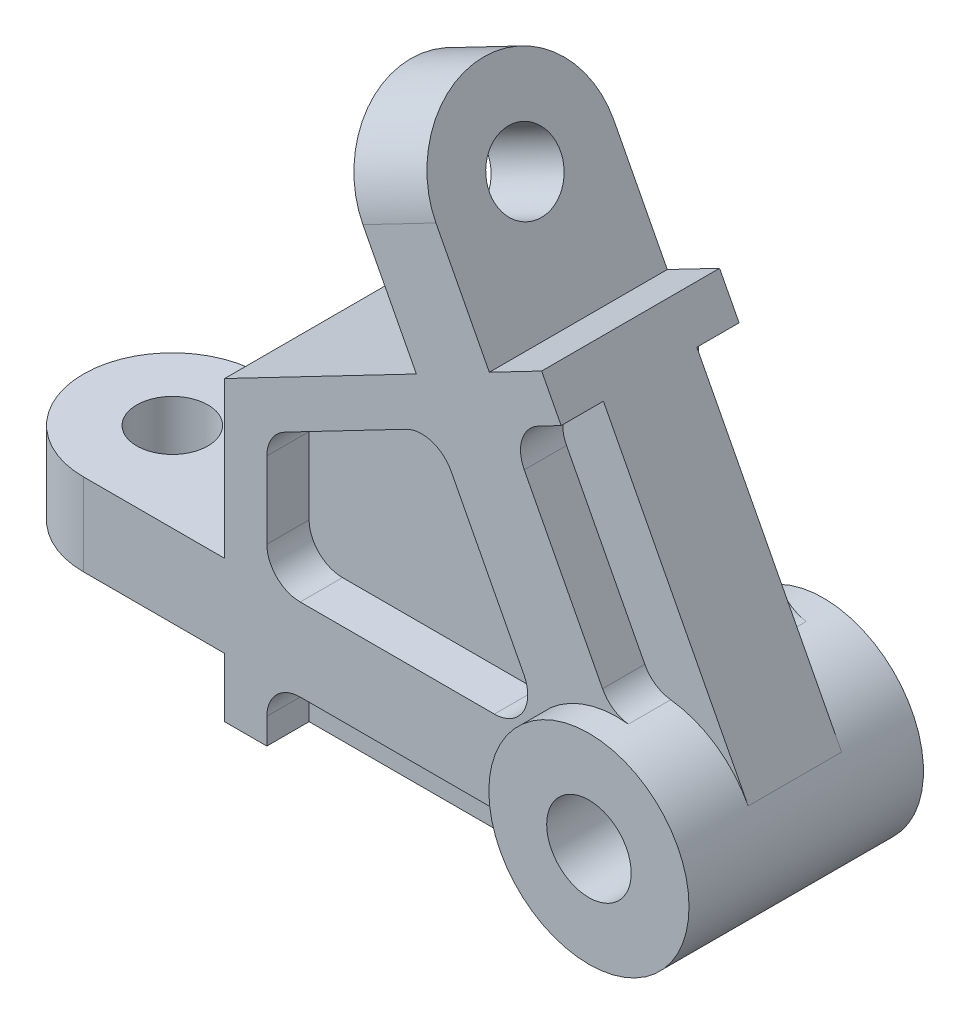
SolidWorks part; units mm, degrees
material "Alliage 1060"
ref_plane "Plan de face" through (0, 0, 0) normal (0, 0, 1) x (1, 0, 0)
ref_plane "Plan de dessus" through (0, 0, 0) normal (0, 1, 0) x (1, 0, 0)
ref_plane "Plan de droite" through (0, 0, 0) normal (1, 0, 0) x (0, 0, -1)
sketch "Esquisse1" plane through (0, 0, 0) normal (0, 0, 1) x (1, 0, 0)
  line L0 (19.9577, 10.3893) -> (-16.9819, 81.3498)
  line L1 (-16.9819, 81.3498) -> (-28.7348, 75.2316)
  line L2 (-28.7348, 75.2316) -> (-49.9755, 116.0345)
  line L3 (-49.9755, 116.0345) -> (-66.3852, 107.4922)
  line L4 (-66.3852, 107.4922) -> (-45.1445, 66.6893)
  line L5 (-45.1445, 66.6893) -> (-88.25, 44.25)
  line L6 (-88.25, 44.25) -> (-88.25, 9.25)
  line L7 (-88.25, 9.25) -> (-140, 9.25)
  line L8 (-140, 9.25) -> (-140, -9.25)
  line L9 (-140, -9.25) -> (-88.25, -9.25)
  line L10 (-88.25, -9.25) -> (-88.25, -22.5605)
  line L11 (-88.25, -22.5605) -> (0.0154, -22.5)
  line L12 (0, 0) -> (-140, 0)
  line L13 (0, 0) -> (-58.1803, 111.7634)
  circle A0 centre (0, 0) radius 22.5
  circle A1 centre (0, 0) radius 9.5
  dimension "D1" = 19
  dimension "D2" = 45
  dimension "D3" = 18.5
  dimension "D4" = 18.5
  dimension "D5" = 9.25
  dimension "D6" = 62.5
  dimension "D7" = 35
  dimension "D8" = 140
  dimension "D9" = 126
  dimension "D10" = 0
  dimension "D11" = 0
  dimension "D12" = 51.75
extrude "Boss.-Extru.1" add sketch "Esquisse1" along normal blind 40 contours A0 L0 L1 L2 L3 L13 | A0 L13 L3 L4 L5 L6 L7 L8 L12 | A0 L12 L8 L9 L10 L11 | A1 L12 A0 L13 | A1 L13 A0 L12
sketch "Esquisse2" plane through (8.2049, 4.2712, 0) normal (0.887, 0.4617, 0) x (0, 0, -1)
  line L0 (-40, 126) -> (0, 126) construction
  line L1 (0, 79.9995) -> (0, 126) construction
  line L6 (0, 79.9995) -> (0, 126)
  line L7 (0, 126) -> (-40, 126)
  line L8 (-40, 126) -> (-40, 79.9995)
  line L9 (-40, 79.9995) -> (0, 79.9995)
  line L10 (0, 79.9995) -> (0, 126)
  line L11 (0, 126) -> (-40, 126)
  line L12 (-40, 126) -> (-40, 79.9995)
  line L13 (-40, 79.9995) -> (0, 79.9995)
  circle A0 centre (-20, 106) radius 8
  circle A1 centre (-20, 106) radius 20
  line M8 (0, 126) -> (-40, 126)
  line M9 (-40, 126) -> (-40, 79.9995)
  dimension "D1" = 16
  dimension "D2" = 40
  dimension "D3" = 0
extrude "Enlèv. mat.-Extru.1" cut sketch "Esquisse2" against normal through all contours A0 | A1 L11 M9 | A1 L10 M8
sketch "Esquisse3" plane through (0, 9.25, 0) normal (0, 1, 0) x (1, 0, 0)
  line L0 (-140, -40) -> (-140, 0) construction
  line L1 (-88.25, 0) -> (-140, 0) construction
  line L6 (-88.25, 0) -> (-140, 0)
  line L7 (-140, 0) -> (-140, -40)
  line L8 (-140, -40) -> (-88.25, -40)
  line L9 (-88.25, -40) -> (-88.25, 0)
  line L10 (-88.25, 0) -> (-140, 0)
  line L11 (-140, 0) -> (-140, -40)
  line L12 (-140, -40) -> (-88.25, -40)
  line L13 (-88.25, -40) -> (-88.25, 0)
  circle A0 centre (-120, -20) radius 8
  circle A1 centre (-120, -20) radius 20
  line M8 (-140, 0) -> (-140, -40)
  line M9 (-140, -40) -> (-88.25, -40)
  dimension "D1" = 40
  dimension "D2" = 16
  dimension "D3" = 0
extrude "Enlèv. mat.-Extru.2" cut sketch "Esquisse3" against normal through all contours A1 L10 M8 | A1 L11 M9 | A0
sketch "Esquisse4" plane through (0, 0, 40) normal (0, 0, 1) x (1, 0, 0)
  line L0 (19.9577, 10.3893) -> (-16.9819, 81.3498) construction
  line L1 (-16.9819, 81.3498) -> (-28.7348, 75.2316) construction
  line L2 (-28.7348, 75.2316) -> (-49.9755, 116.0345) construction
  line L3 (-49.9755, 116.0345) -> (-66.3852, 107.4922) construction
  line L4 (-66.3852, 107.4922) -> (-45.1445, 66.6893) construction
  line L5 (-45.1445, 66.6893) -> (-88.25, 44.25) construction
  line L6 (-88.25, 44.25) -> (-88.25, 9.25) construction
  line L7 (-88.25, 9.25) -> (-140, 9.25) construction
  line L8 (-140, 9.25) -> (-140, -9.25) construction
  line L9 (-140, -9.25) -> (-88.25, -9.25) construction
  line L10 (-88.25, -9.25) -> (-88.25, -22.5605) construction
  line L11 (-88.25, -22.5605) -> (0.0154, -22.5) construction
  line L12 (0, 0) -> (-140, 0) construction
  line L13 (0, 0) -> (-58.1803, 111.7634) construction
  line L14 (19.9577, 10.3893) -> (-16.9819, 81.3498)
  line L15 (-16.9819, 81.3498) -> (-28.7348, 75.2316)
  line L16 (-28.7348, 75.2316) -> (-49.9755, 116.0345)
  line L17 (-49.9755, 116.0345) -> (-66.3852, 107.4922)
  line L18 (-66.3852, 107.4922) -> (-45.1445, 66.6893)
  line L19 (-45.1445, 66.6893) -> (-88.25, 44.25)
  line L20 (-88.25, 44.25) -> (-88.25, 9.25)
  line L21 (-88.25, 9.25) -> (-140, 9.25)
  line L22 (-140, 9.25) -> (-140, -9.25)
  line L23 (-140, -9.25) -> (-88.25, -9.25)
  line L24 (-88.25, -9.25) -> (-88.25, -22.5605)
  line L25 (-88.25, -22.5605) -> (0.0154, -22.5)
  line L26 (0, 0) -> (-140, 0)
  line L27 (0, 0) -> (-58.1803, 111.7634)
  circle A1 centre (0, 0) radius 22.5
  circle A2 centre (0, 0) radius 22.5
  circle A3 centre (0, 0) radius 9.5
  circle A4 centre (0, 0) radius 9.5
  arc M7 (0.0154, -22.5) -> (19.9577, 10.3893) centre (0, 0) ccw
  circle M16 centre (0, 0) radius 9.5
  dimension "D1" = 0
  dimension "D2" = 0
extrude "Boss.-Extru.2" add sketch "Esquisse4" along normal blind 6.35 contours A2 L27 L26 M7 M16 | L27 A2 L26 M16
sketch "Esquisse5" plane through (0, 0, 0) normal (0, 0, -1) x (-1, 0, 0)
  line L0 (-19.9577, 10.3893) -> (16.9819, 81.3498) construction
  line L1 (16.9819, 81.3498) -> (28.7348, 75.2316) construction
  line L2 (28.7348, 75.2316) -> (49.9755, 116.0345) construction
  line L3 (49.9755, 116.0345) -> (66.3852, 107.4922) construction
  line L4 (66.3852, 107.4922) -> (45.1445, 66.6893) construction
  line L5 (45.1445, 66.6893) -> (88.25, 44.25) construction
  line L6 (88.25, 44.25) -> (88.25, 9.25) construction
  line L7 (88.25, 9.25) -> (140, 9.25) construction
  line L8 (140, 9.25) -> (140, -9.25) construction
  line L9 (140, -9.25) -> (88.25, -9.25) construction
  line L10 (88.25, -9.25) -> (88.25, -22.5605) construction
  line L11 (88.25, -22.5605) -> (-0.0154, -22.5) construction
  line L12 (0, 0) -> (140, 0) construction
  line L13 (0, 0) -> (58.1803, 111.7634) construction
  line L14 (-19.9577, 10.3893) -> (16.9819, 81.3498)
  line L15 (16.9819, 81.3498) -> (28.7348, 75.2316)
  line L16 (28.7348, 75.2316) -> (49.9755, 116.0345)
  line L17 (49.9755, 116.0345) -> (66.3852, 107.4922)
  line L18 (66.3852, 107.4922) -> (45.1445, 66.6893)
  line L19 (45.1445, 66.6893) -> (88.25, 44.25)
  line L20 (88.25, 44.25) -> (88.25, 9.25)
  line L21 (88.25, 9.25) -> (140, 9.25)
  line L22 (140, 9.25) -> (140, -9.25)
  line L23 (140, -9.25) -> (88.25, -9.25)
  line L24 (88.25, -9.25) -> (88.25, -22.5605)
  line L25 (88.25, -22.5605) -> (-0.0154, -22.5)
  line L26 (0, 0) -> (140, 0)
  line L27 (0, 0) -> (58.1803, 111.7634)
  circle A1 centre (0, 0) radius 22.5
  circle A2 centre (0, 0) radius 22.5
  circle A3 centre (0, 0) radius 9.5
  circle A4 centre (0, 0) radius 9.5
  arc M13 (-19.9577, 10.3893) -> (-0.0154, -22.5) centre (0, 0) ccw
  circle M16 centre (0, 0) radius 9.5
  dimension "D1" = 0
  dimension "D2" = 0
extrude "Boss.-Extru.3" add sketch "Esquisse5" along normal blind 6.35 contours L26 A2 L27 M16 | L27 A2 L26 M13 M16
sketch "Esquisse6" plane through (0, 0, 40) normal (0, 0, 1) x (1, 0, 0)
  line L0 (-12.5953, 72.9232) -> (-17.6956, 70.2681)
  line L1 (19.9577, 10.3893) -> (-16.9819, 81.3498) construction
  line L2 (-20.8851, 60.1525) -> (-3.2874, 26.3475)
  line L3 (-88.25, -22.5605) -> (0.0154, -22.5) construction
  line L4 (-16.9819, 81.3498) -> (-28.7348, 75.2316) construction
  line L5 (-28.7348, 75.2316) -> (-40.7405, 98.2943) construction
  line L6 (-40.7405, 98.2943) -> (-57.1502, 89.752) construction
  line L7 (-57.1502, 89.752) -> (-45.1445, 66.6893) construction
  line L8 (-45.1445, 66.6893) -> (-88.25, 44.25) construction
  line L9 (-88.25, 44.25) -> (-88.25, 9.25) construction
  line L10 (-88.25, 9.25) -> (-120, 9.25) construction
  line L11 (-120, 9.25) -> (-120, -9.25) construction
  line L12 (-120, -9.25) -> (-88.25, -9.25) construction
  line L13 (-88.25, -9.25) -> (-88.25, -22.5605) construction
  line L14 (-88.25, -22.5605) -> (0.0154, -22.5)
  line L15 (19.9577, 10.3893) -> (-16.9819, 81.3498)
  line L16 (-16.9819, 81.3498) -> (-28.7348, 75.2316)
  line L17 (-28.7348, 75.2316) -> (-40.7405, 98.2943)
  line L18 (-40.7405, 98.2943) -> (-57.1502, 89.752)
  line L19 (-57.1502, 89.752) -> (-45.1445, 66.6893)
  line L20 (-45.1445, 66.6893) -> (-88.25, 44.25)
  line L21 (-88.25, 44.25) -> (-88.25, 9.25)
  line L22 (-88.25, 9.25) -> (-120, 9.25)
  line L23 (-120, 9.25) -> (-120, -9.25)
  line L24 (-120, -9.25) -> (-88.25, -9.25)
  line L25 (-88.25, -9.25) -> (-88.25, -22.5605)
  line L26 (-37.2948, 51.6101) -> (-20.9506, 20.2131)
  line L27 (-27.6031, 9.25) -> (-71.25, 9.25)
  line L28 (-78.75, 16.75) -> (-78.75, 33.9341)
  line L29 (-74.7131, 40.5867) -> (-47.4105, 54.7996)
  line L30 (-78.75, -22.554) -> (-78.75, -16.75)
  line L31 (-71.25, -9.25) -> (-24.8885, -9.25)
  line L32 (0, 0) -> (-120, 0)
  line L33 (0, 0) -> (-48.9454, 94.0231)
  arc A0 (-17.6956, 70.2681) -> (-20.8851, 60.1525) centre (-14.2325, 63.6156) ccw
  circle A1 centre (0, 0) radius 22.5 construction
  arc A2 (19.9577, 10.3893) -> (0.0154, -22.5) centre (0, 0) ccw construction
  arc A3 (-18.6664, -12.5625) -> (2.5239, 22.358) centre (0, 0) ccw
  arc A4 (19.9577, 10.3893) -> (-1.2659, 22.4644) centre (0, 0) ccw
  arc A5 (-20.9506, 20.2131) -> (-27.6031, 9.25) centre (-27.6031, 16.75) cw
  arc A6 (-37.2948, 51.6101) -> (-47.4105, 54.7996) centre (-43.9474, 48.147) ccw
  arc A7 (-71.25, 9.25) -> (-78.75, 16.75) centre (-71.25, 16.75) cw
  arc A8 (-78.75, 33.9341) -> (-74.7131, 40.5867) centre (-71.25, 33.9341) cw
  arc A9 (-78.75, -16.75) -> (-71.25, -9.25) centre (-71.25, -16.75) cw
  arc A10 (-10.3893, 19.9577) -> (-22.5, 0) centre (0, 0) ccw
  arc A11 (-10.3893, 19.9577) -> (-22.5, 0) centre (0, 0) ccw
  arc A12 (-20.5107, -9.25) -> (0.0154, -22.5) centre (0, 0) ccw
  arc A13 (-3.2874, 26.3475) -> (2.5239, 22.358) centre (3.3652, 29.8107) ccw
  arc A14 (-24.8885, -9.25) -> (-18.6664, -12.5625) centre (-24.8885, -16.75) cw
  arc M30 (0.0154, -22.5) -> (19.9577, 10.3893) centre (0, 0) cw
  line M31 (19.9577, 10.3893) -> (-16.9819, 81.3498)
  dimension "D1" = 7.5
  dimension "D2" = 7.5
  dimension "D5" = 7.5
  dimension "D10" = 7.5
  dimension "D13" = 7.5
  dimension "D3" = 9.5
  dimension "D4" = 9.5
  dimension "D6" = 9.5
  dimension "D7" = 9.25
  dimension "D8" = 9.25
  dimension "D9" = 9.25
  dimension "D11" = 9.25
  dimension "D12" = 9.5
extrude "Enlèv. mat.-Extru.3" cut sketch "Esquisse6" against normal blind 9.5 contours A8 L28 A7 L27 A5 L26 A6 L29 | L0 A0 L2 M30 M31 | A9 L30 L14 L31 M30
sketch "Esquisse9" plane through (0, 0, 0) normal (0, 0, -1) x (-1, 0, 0)
  line L0 (24.8885, -9.25) -> (71.25, -9.25) construction
  line L1 (78.75, -16.75) -> (78.75, -22.554) construction
  line L2 (78.75, -22.554) -> (-0.0154, -22.5) construction
  line L3 (20.8851, 60.1525) -> (3.2874, 26.3475) construction
  line L4 (-19.9577, 10.3893) -> (12.5953, 72.9232) construction
  line L5 (12.5953, 72.9232) -> (17.6956, 70.2681) construction
  line L6 (78.75, 33.9341) -> (78.75, 16.75) construction
  line L7 (71.25, 9.25) -> (27.6031, 9.25) construction
  line L8 (20.9506, 20.2131) -> (37.2948, 51.6101) construction
  line L9 (47.4105, 54.7996) -> (74.7131, 40.5867) construction
  line L10 (-0.0154, -22.5) -> (88.25, -22.5605) construction
  line L11 (88.25, -22.5605) -> (88.25, -9.25) construction
  line L12 (88.25, -9.25) -> (120, -9.25) construction
  line L13 (120, -9.25) -> (120, 9.25) construction
  line L14 (120, 9.25) -> (88.25, 9.25) construction
  line L15 (88.25, 9.25) -> (88.25, 44.25) construction
  line L16 (88.25, 44.25) -> (45.1445, 66.6893) construction
  line L17 (45.1445, 66.6893) -> (57.1502, 89.752) construction
  line L18 (57.1502, 89.752) -> (40.7405, 98.2943) construction
  line L19 (40.7405, 98.2943) -> (28.7348, 75.2316) construction
  line L20 (28.7348, 75.2316) -> (16.9819, 81.3498) construction
  line L21 (16.9819, 81.3498) -> (-19.9577, 10.3893) construction
  line L22 (24.8885, -9.25) -> (71.25, -9.25)
  line L23 (78.75, -16.75) -> (78.75, -22.554)
  line L24 (78.75, -22.554) -> (-0.0154, -22.5)
  line L25 (20.8851, 60.1525) -> (3.2874, 26.3475)
  line L26 (-19.9577, 10.3893) -> (12.5953, 72.9232)
  line L27 (12.5953, 72.9232) -> (17.6956, 70.2681)
  line L28 (78.75, 33.9341) -> (78.75, 16.75)
  line L29 (71.25, 9.25) -> (27.6031, 9.25)
  line L30 (20.9506, 20.2131) -> (37.2948, 51.6101)
  line L31 (47.4105, 54.7996) -> (74.7131, 40.5867)
  line L32 (-0.0154, -22.5) -> (88.25, -22.5605)
  line L33 (88.25, -22.5605) -> (88.25, -9.25)
  line L34 (88.25, -9.25) -> (120, -9.25)
  line L35 (120, -9.25) -> (120, 9.25)
  line L36 (120, 9.25) -> (88.25, 9.25)
  line L37 (88.25, 9.25) -> (88.25, 44.25)
  line L38 (88.25, 44.25) -> (45.1445, 66.6893)
  line L39 (45.1445, 66.6893) -> (57.1502, 89.752)
  line L40 (57.1502, 89.752) -> (40.7405, 98.2943)
  line L41 (40.7405, 98.2943) -> (28.7348, 75.2316)
  line L42 (28.7348, 75.2316) -> (16.9819, 81.3498)
  line L43 (16.9819, 81.3498) -> (-19.9577, 10.3893)
  arc A2 (24.8885, -9.25) -> (18.6664, -12.5625) centre (24.8885, -16.75) ccw construction
  arc A3 (78.75, -16.75) -> (71.25, -9.25) centre (71.25, -16.75) ccw construction
  arc A4 (-0.0154, -22.5) -> (18.6664, -12.5625) centre (0, 0) ccw construction
  arc A5 (-2.5239, 22.358) -> (3.2874, 26.3475) centre (-3.3652, 29.8107) ccw construction
  arc A6 (-2.5239, 22.358) -> (-19.9577, 10.3893) centre (0, 0) ccw construction
  arc A7 (20.8851, 60.1525) -> (17.6956, 70.2681) centre (14.2325, 63.6156) ccw construction
  arc A8 (78.75, 33.9341) -> (74.7131, 40.5867) centre (71.25, 33.9341) ccw construction
  arc A9 (71.25, 9.25) -> (78.75, 16.75) centre (71.25, 16.75) ccw construction
  arc A10 (20.9506, 20.2131) -> (27.6031, 9.25) centre (27.6031, 16.75) ccw construction
  arc A11 (47.4105, 54.7996) -> (37.2948, 51.6101) centre (43.9474, 48.147) ccw construction
  arc A12 (-0.0154, -22.5) -> (-19.9577, 10.3893) centre (0, 0) ccw construction
  arc A13 (24.8885, -9.25) -> (18.6664, -12.5625) centre (24.8885, -16.75) ccw
  arc A14 (78.75, -16.75) -> (71.25, -9.25) centre (71.25, -16.75) ccw
  arc A15 (-0.0154, -22.5) -> (18.6664, -12.5625) centre (0, 0) ccw
  arc A16 (-2.5239, 22.358) -> (3.2874, 26.3475) centre (-3.3652, 29.8107) ccw
  arc A17 (-2.5239, 22.358) -> (-19.9577, 10.3893) centre (0, 0) ccw
  arc A18 (20.8851, 60.1525) -> (17.6956, 70.2681) centre (14.2325, 63.6156) ccw
  arc A19 (78.75, 33.9341) -> (74.7131, 40.5867) centre (71.25, 33.9341) ccw
  arc A20 (71.25, 9.25) -> (78.75, 16.75) centre (71.25, 16.75) ccw
  arc A21 (20.9506, 20.2131) -> (27.6031, 9.25) centre (27.6031, 16.75) ccw
  arc A22 (47.4105, 54.7996) -> (37.2948, 51.6101) centre (43.9474, 48.147) ccw
  arc A23 (-0.0154, -22.5) -> (-19.9577, 10.3893) centre (0, 0) ccw
  arc M15 (-19.9577, 10.3893) -> (-0.0154, -22.5) centre (0, 0) cw
  line M16 (-0.0154, -22.5) -> (88.25, -22.5605)
  line M27 (16.9819, 81.3498) -> (-19.9577, 10.3893)
extrude "Enlèv. mat.-Extru.6" cut sketch "Esquisse9" against normal blind 9.5 contours L25 A18 L27 A16 M27 M15 | L31 A22 L30 A21 L29 A20 L28 A19 | L23 A14 L22 A13 M15 M16
equation "\"A\" = 106"
equation "\"B\" = 18.5"
equation "\"C\"= 62.5"
equation "\"D3@Esquisse1\"=\"B\""
equation "\"D8@Esquisse6\"=\"B\"/2"
equation "\"D4@Esquisse1\"=\"B\""
equation "\"D5@Esquisse1\"=\"B\"/2"
equation "\"D9@Esquisse1\"=\"A\"+20"
equation "\"D6@Esquisse1\"=\"C\""
equation "\"D11@Esquisse6\"=\"B\"/2"
equation "\"D7@Esquisse6\"=\"B\"/2"
equation "\"D9@Esquisse6\"=\"B\"/2"
